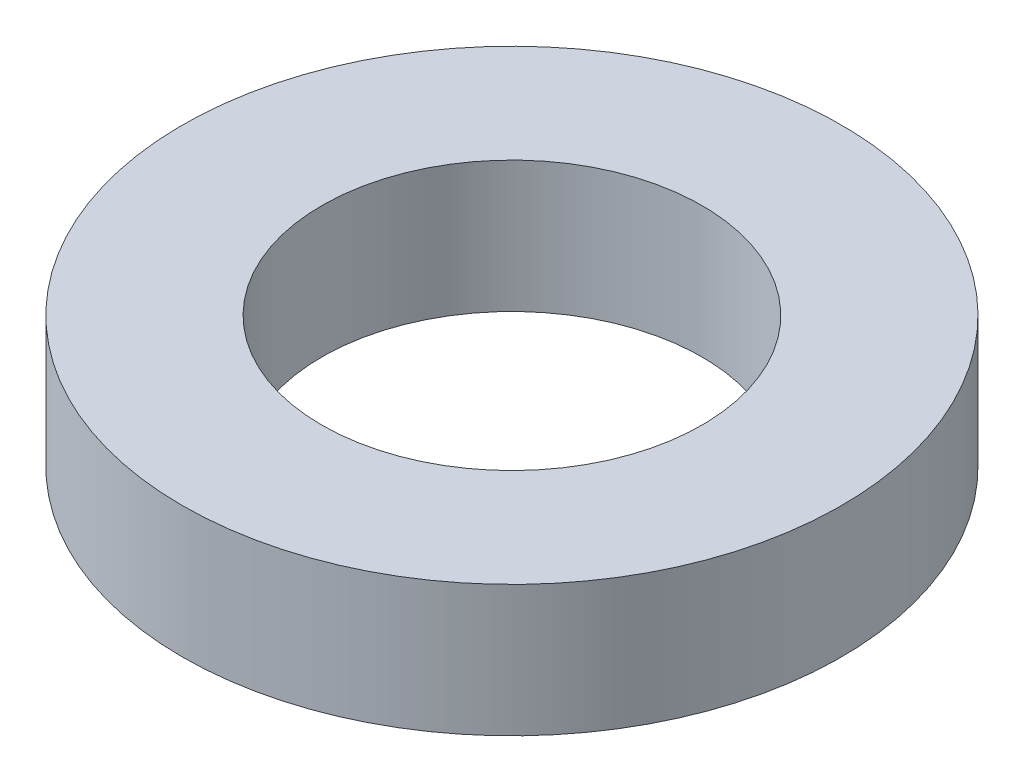
SolidWorks part; units mm, degrees
ref_plane "Front Plane" through (0, 0, 0) normal (0, 0, 1) x (1, 0, 0)
ref_plane "Top Plane" through (0, 0, 0) normal (0, 1, 0) x (1, 0, 0)
ref_plane "Right Plane" through (0, 0, 0) normal (1, 0, 0) x (0, 0, -1)
sketch "Sketch1" plane through (0, 0, 0) normal (0, 1, 0) x (1, 0, 0)
  circle A0 centre (0, 0) radius 16.51
  circle A1 centre (0, 0) radius 9.525
  dimension "D1" = 19.05
  dimension "D2" = 33.02
extrude "Boss-Extrude1" add sketch "Sketch1" along normal blind 6.57
